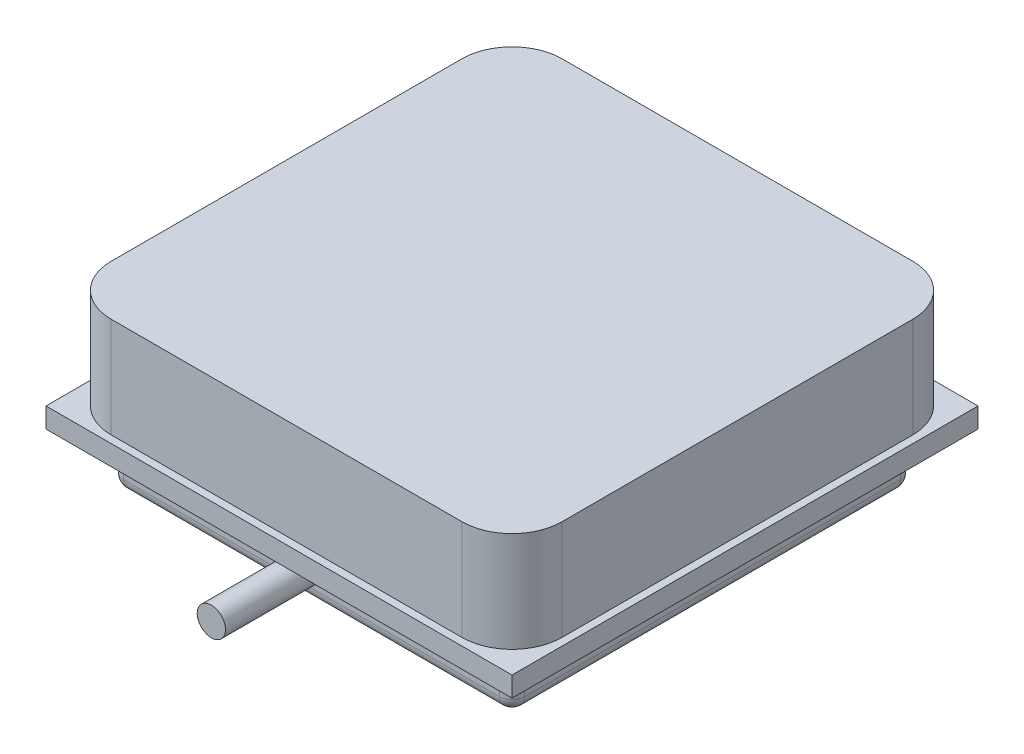
SolidWorks part; units mm, degrees
ref_plane "Front Plane" through (0, 0, 0) normal (0, 0, 1) x (1, 0, 0)
ref_plane "Top Plane" through (0, 0, 0) normal (0, 1, 0) x (1, 0, 0)
ref_plane "Right Plane" through (0, 0, 0) normal (1, 0, 0) x (0, 0, -1)
sketch "Sketch1" plane through (0, 0, 0) normal (0, 1, 0) x (1, 0, 0)
  line L1 (-9.3, 9.3) -> (9.3, 9.3)
  line L2 (-9.3, 9.3) -> (-9.3, -9.3)
  line L3 (-9.3, -9.3) -> (9.3, -9.3)
  line L4 (9.3, 9.3) -> (9.3, -9.3)
  line L5 (-9.3, 9.3) -> (9.3, -9.3) construction
  line L6 (-9.3, -9.3) -> (9.3, 9.3) construction
  point P0 (0, 0)
  dimension "D1" = 18.6
extrude "PCB" add sketch "Sketch1" along normal blind 0.8
sketch "Sketch2" plane through (0, 0.8, 0) normal (0, 1, 0) x (1, 0, 0)
  line L1 (-9, 9) -> (9, 9)
  line L2 (-9, 9) -> (-9, -9)
  line L3 (-9, -9) -> (9, -9)
  line L4 (9, 9) -> (9, -9)
  line L5 (-9, 9) -> (9, -9) construction
  line L6 (-9, -9) -> (9, 9) construction
  point P0 (0, 0)
  dimension "D1" = 18
extrude "PATCH" add sketch "Sketch2" along normal blind 4
sketch "Sketch3" plane through (0, 0, 0) normal (0, -1, 0) x (1, 0, 0)
  line L1 (-8, 8) -> (8, 8)
  line L2 (-8, 8) -> (-8, -8)
  line L3 (-8, -8) -> (8, -8)
  line L4 (8, 8) -> (8, -8)
  line L5 (-8, 8) -> (8, -8) construction
  line L6 (-8, -8) -> (8, 8) construction
  point P0 (0, 0)
  dimension "D1" = 16
extrude "RADOME" add sketch "Sketch3" along normal blind 2
fillet "Fillet1" radius 2 4 edges at (-9, 2.8, -9) (9, 2.8, -9) (9, 2.8, 9) (-9, 2.8, 9)
fillet "Fillet2" radius 0.5 8 edges at (0, -2, -8) (-8, -2, 0) (0, -2, 8) (8, -2, 0) (-8, -1, -8) (8, -1, -8) (8, -1, 8) (-8, -1, 8)
sketch "Sketch4" plane through (0, 0, 0) normal (0, 0, 1) x (1, 0, 0)
  circle A0 centre (0, -0.65) radius 0.565
  point P2 (0, 0)
  point P4 (0, -0.6413)
  dimension "D1" = 1.13
  dimension "D2" = 0.65
extrude "CABLE" add sketch "Sketch4" along normal blind 12
